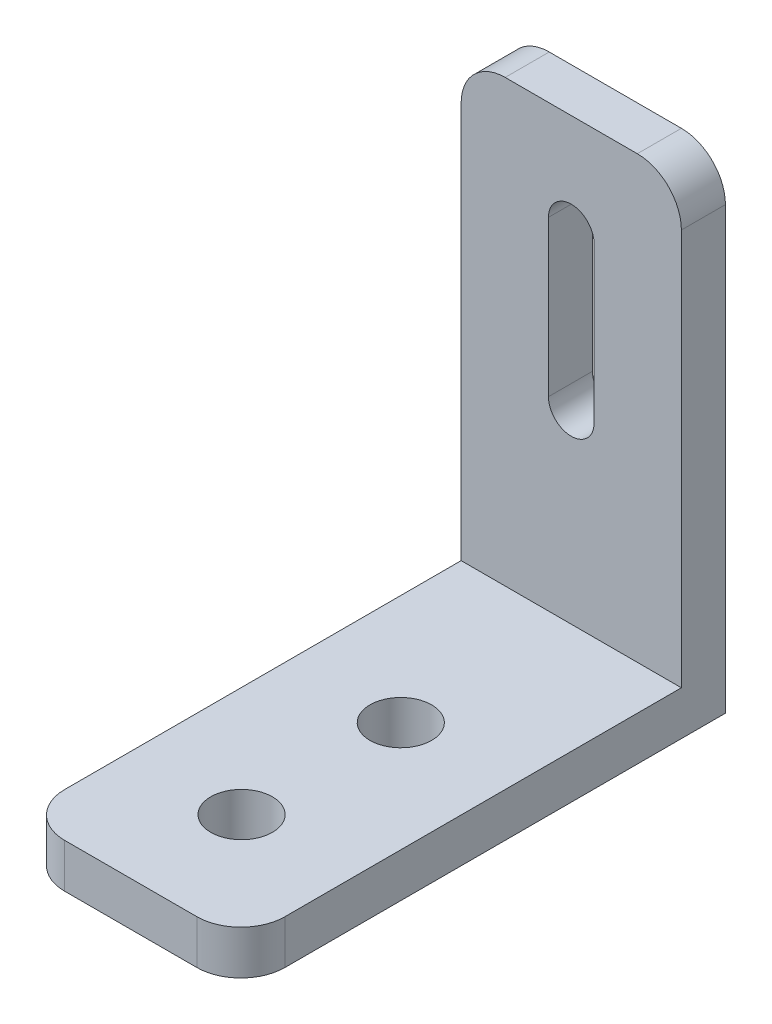
SolidWorks part; units mm, degrees
ref_plane "Front Plane" through (0, 0, 0) normal (0, 0, 1) x (1, 0, 0)
ref_plane "Top Plane" through (0, 0, 0) normal (0, 1, 0) x (1, 0, 0)
ref_plane "Right Plane" through (0, 0, 0) normal (1, 0, 0) x (0, 0, -1)
sketch "Sketch1" plane through (0, 0, 0) normal (1, 0, 0) x (0, 0, -1)
  line L0 (0, 0) -> (100, 0)
  line L5 (100, 0) -> (100, 100)
  point P2 (0, 0)
extrude "Extrude-Thin1" add sketch "Sketch1" along normal blind 50 thin contours L0 L5
fillet "Fillet1" radius 10 4 edges at (0, 100, -105) (50, 100, -105) (50, -5, 0) (0, -5, 0)
sketch "Sketch2" plane through (0, 0, -100) normal (0, 0, 1) x (1, 0, 0)
  line L0 (25, 77.3929) -> (25, 42.1362) construction
  line L1 (30.1845, 77.3929) -> (30.1845, 42.1362)
  line L2 (19.8155, 77.3929) -> (19.8155, 42.1362)
  arc A0 (30.1845, 77.3929) -> (19.8155, 77.3929) centre (25, 77.3929) ccw
  arc A1 (19.8155, 42.1362) -> (30.1845, 42.1362) centre (25, 42.1362) ccw
  point P2 (25, 59.7646)
extrude "Cut-Extrude1" cut sketch "Sketch2" against normal blind 10
sketch "Sketch3" plane through (0, 0, 0) normal (0, 1, 0) x (1, 0, 0)
  circle A0 centre (25, 25.1527) radius 7
  circle A1 centre (25, 61.3004) radius 7
extrude "Cut-Extrude2" cut sketch "Sketch3" against normal blind 10
